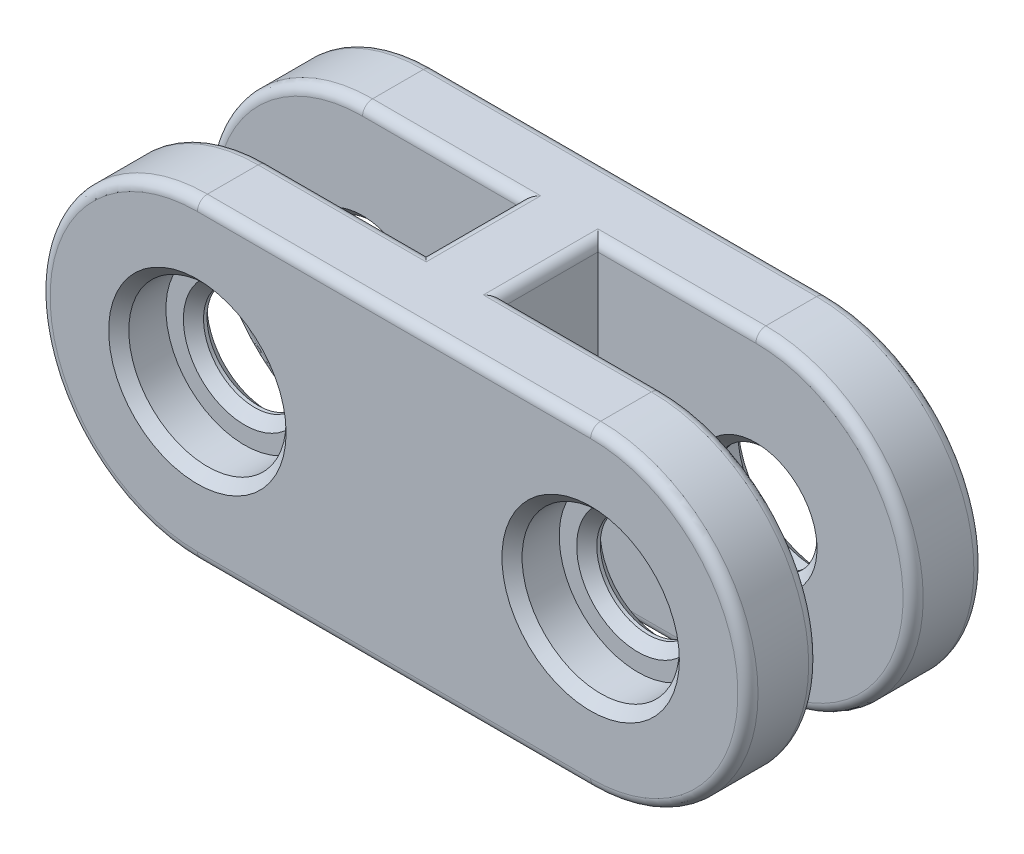
SolidWorks part; units mm, degrees
ref_plane "Front Plane" through (0, 0, 0) normal (0, 0, 1) x (1, 0, 0)
ref_plane "Top Plane" through (0, 0, 0) normal (0, 1, 0) x (1, 0, 0)
ref_plane "Right Plane" through (0, 0, 0) normal (1, 0, 0) x (0, 0, -1)
sketch "Sketch1" plane through (0, 0, 0) normal (0, 0, 1) x (1, 0, 0)
  line L0 (0, 0) -> (31.75, 0) construction
  line L1 (0, 12.7) -> (31.75, 12.7)
  line L2 (0, -12.7) -> (31.75, -12.7)
  arc A0 (0, 12.7) -> (0, -12.7) centre (0, 0) ccw
  arc A1 (31.75, -12.7) -> (31.75, 12.7) centre (31.75, 0) ccw
  circle A2 centre (0, 0) radius 4.1275
  circle A3 centre (31.75, 0) radius 4.1275
  point P3 (15.875, 0)
  dimension "D2" = 12.7
  dimension "D1" = 31.75
extrude "Boss-Extrude2" add sketch "Sketch1" along normal mid plane 19.05
sketch "Sketch3" plane through (0, 0, 9.525) normal (0, 0, 1) x (1, 0, 0)
  circle A0 centre (0, 0) radius 6.35
  circle A1 centre (31.75, 0) radius 6.35
  dimension "D1" = 12.7
extrude "Cut-Extrude1" cut sketch "Sketch3" against normal blind 3.81
mirror "Mirror1" about plane through (0, 0, 0) normal (0, 0, 1) of "Cut-Extrude1"
sketch "Sketch4" plane through (0, 12.7, 0) normal (0, 1, 0) x (1, 0, 0)
  line L0 (0, 0) -> (15.875, 0) construction
  line L1 (52.4197, 3.81) -> (52.4197, -3.81)
  line L2 (-20.6697, 3.81) -> (12.7539, 3.81)
  line L3 (15.875, -9.525) -> (15.875, 9.525) construction
  line L4 (31.75, -9.525) -> (0, -9.525) construction
  line L5 (31.75, 9.525) -> (0, 9.525) construction
  line L6 (-20.6697, 3.81) -> (-20.6697, -3.81)
  line L7 (-20.6697, -3.81) -> (12.7539, -3.81)
  line L8 (12.7539, 3.81) -> (12.7539, -3.81)
  line L9 (52.4197, 3.81) -> (18.9961, 3.81)
  line L10 (18.9961, 3.81) -> (18.9961, -3.81)
  line L11 (52.4197, -3.81) -> (18.9961, -3.81)
  dimension "D1" = 7.62
  dimension "D2" = 6.2423
extrude "Cut-Extrude3" cut sketch "Sketch4" against normal through all
fillet "Fillet3" radius 0.8128 24 edges at (-12.7, 0, -9.525) (15.875, -12.7, -9.525) (15.875, 12.7, -9.525) (44.45, 0, -9.525) (44.45, 0, 3.81) (25.3731, -12.7, -3.81) (44.45, 0, -3.81) (25.3731, 12.7, -3.81) (12.7539, 12.7, 0) (18.9961, 12.7, 0) (25.3731, 12.7, 3.81) (25.3731, -12.7, 3.81) (18.9961, -12.7, 0) (44.45, 0, 9.525) (15.875, -12.7, 9.525) (-12.7, 0, 9.525) (15.875, 12.7, 9.525) (12.7539, -12.7, 0) (6.3769, -12.7, -3.81) (6.3769, -12.7, 3.81) (-12.7, 0, 3.81) (-12.7, 0, -3.81) (6.3769, 12.7, -3.81) (6.3769, 12.7, 3.81)
chamfer "Chamfer5" distance 0.8128 angle 45 12 edges at (4.1275, 0, 3.81) (-4.1275, 0, -3.81) (-4.1275, 0, -5.715) (27.6225, 0, -5.715) (6.35, 0, 9.525) (38.1, 0, 9.525) (27.6225, 0, -3.81) (6.35, 0, -9.525) (38.1, 0, -9.525) (35.8775, 0, 3.81) (35.8775, 0, 5.715) (4.1275, 0, 5.715)
